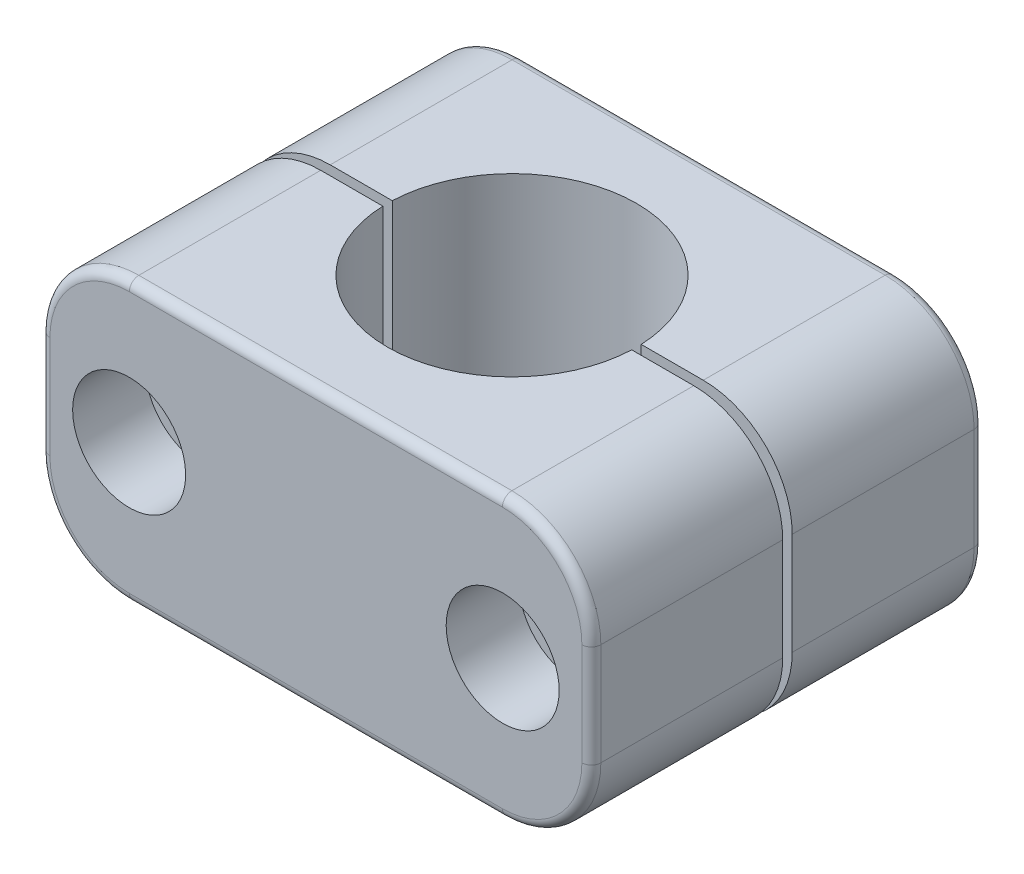
SolidWorks part; units mm, degrees
ref_plane "Front Plane" through (0, 0, 0) normal (0, 0, 1) x (1, 0, 0)
ref_plane "Top Plane" through (0, 0, 0) normal (0, 1, 0) x (1, 0, 0)
ref_plane "Right Plane" through (0, 0, 0) normal (1, 0, 0) x (0, 0, -1)
sketch "Sketch1" plane through (0, 0, 0) normal (0, 1, 0) x (1, 0, 0)
  line L1 (-29.5, -21) -> (29.5, -21)
  line L2 (-29.5, -21) -> (-29.5, 21)
  line L3 (-29.5, 21) -> (29.5, 21)
  line L4 (29.5, -21) -> (29.5, 21)
  circle A0 centre (0, 0) radius 13.335
  point P4 (29.5, 0)
  point P5 (0, 21)
  dimension "D3" = 26.67
  dimension "D1" = 42
  dimension "D2" = 59
extrude "Extrude1" add sketch "Sketch1" along normal mid plane 30
ref_plane "Plane1" through (20, 0, 0) normal (1, 0, 0) x (0, 0, -1)
sketch "Sketch7" plane through (20, 0, 0) normal (1, 0, 0) x (0, 0, -1)
  line L0 (-28.8, 0) -> (28.8, 0)
  line L1 (28.8, 0) -> (28.8, 6.05)
  line L2 (28.8, 6.05) -> (13.2, 6.05)
  line L3 (13.2, 6.05) -> (13.2, 3.302)
  line L4 (13.2, 3.302) -> (-13.2, 3.302)
  line L5 (-13.2, 3.302) -> (-13.2, 6.05)
  line L6 (-13.2, 6.05) -> (-28.8, 6.05)
  line L7 (-28.8, 6.05) -> (-28.8, 0)
  line L8 (28.8, 0) -> (42.4807, 0) construction
  line L9 (21, 15) -> (21, -15) construction
  line L10 (-21, 15) -> (-21, -15) construction
  point P2 (21, 6.05)
  point P10 (-21, 6.05)
  dimension "D1" = 6.604
  dimension "D2" = 12.1
  dimension "D3" = 7.8
revolve "Cut-Revolve1" cut sketch "Sketch7" angle 360 about L8
mirror "Mirror1" about plane through (0, 0, 0) normal (1, 0, 0) of "Cut-Revolve1"
fillet "Fillet1" radius 9.525 4 edges at (29.5, -15, 0) (-29.5, -15, 0) (29.5, 15, 0) (-29.5, 15, 0)
fillet "Fillet2" radius 1.016 16 edges at (-29.5, 0, 21) (0, -15, 21) (29.5, 0, 21) (0, 15, 21) (-26.7102, 12.2102, 21) (26.7102, 12.2102, 21) (26.7102, -12.2102, 21) (-26.7102, -12.2102, 21) (26.7102, 12.2102, -21) (26.7102, -12.2102, -21) (-26.7102, -12.2102, -21) (-26.7102, 12.2102, -21) (-29.5, 0, -21) (0, -15, -21) (29.5, 0, -21) (0, 15, -21)
sketch "Sketch4" plane through (0, 0, 0) normal (0, 1, 0) x (-1, 0, 0)
  line L3 (38.806, -0.508) -> (-33.7374, -0.508)
  line L4 (38.806, 0.508) -> (-33.7374, 0.508)
  line L5 (38.806, -0.508) -> (38.806, 0.508)
  line L6 (-33.7374, -0.508) -> (-33.7374, 0.508)
  point P0 (38.806, 0)
  dimension "D1" = 1.016
extrude "Cut-Extrude3" cut sketch "Sketch4" against normal mid plane 101.6
